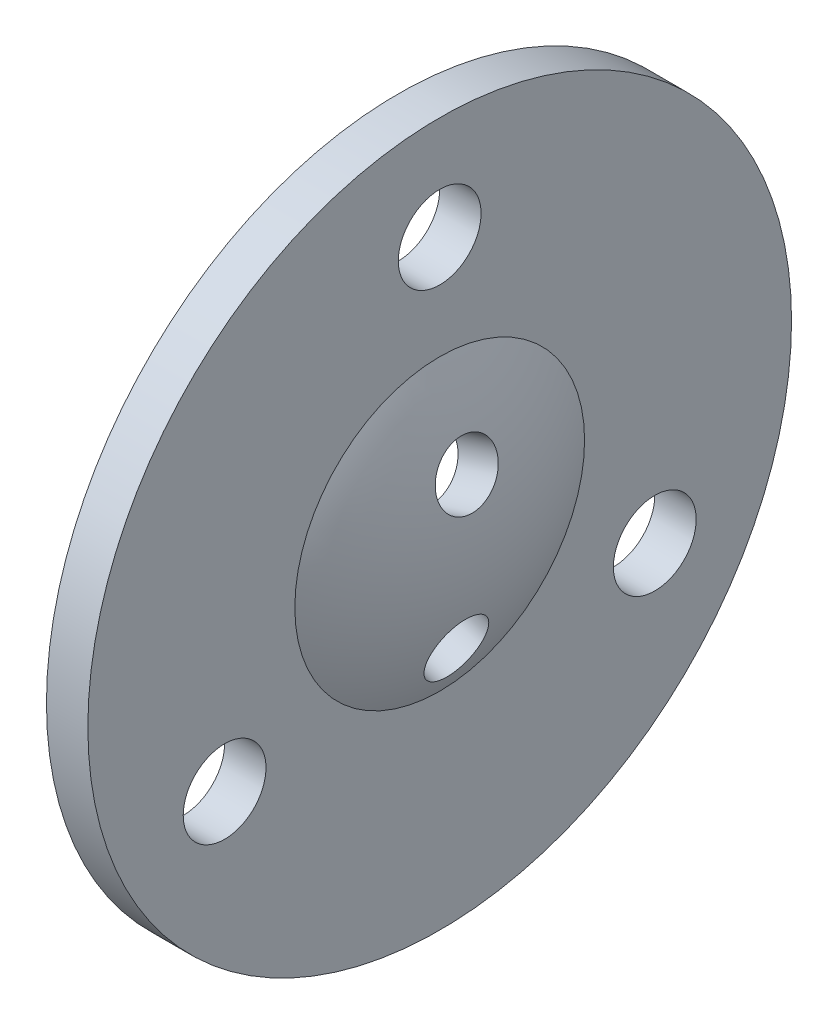
SolidWorks part; units mm, degrees
material "铝棒 LY12"
ref_plane "前视基准面" through (0, 0, 0) normal (0, 0, 1) x (1, 0, 0)
ref_plane "上视基准面" through (0, 0, 0) normal (0, 1, 0) x (1, 0, 0)
ref_plane "右视基准面" through (0, 0, 0) normal (1, 0, 0) x (0, 0, -1)
sketch "草图1" plane through (0, 0, 0) normal (0, 0, 1) x (1, 0, 0)
  line L0 (14.3875, 7) -> (14.3875, 17)
  line L1 (14.3875, 17) -> (12.3875, 17)
  line L2 (12.3875, 17) -> (12.3875, 6.523)
  line L3 (0, 0) -> (19.0099, 0) construction
  line L4 (14, 0) -> (16, 0)
  arc A0 (14, 0) -> (12.3875, 6.523) centre (0, 0) ccw
  arc A1 (16, 0) -> (14.3875, 7) centre (0, 0) ccw
  circle A2 centre (0, 0) radius 16 construction
  circle A3 centre (0, 0) radius 14 construction
  dimension "D2" = 28
  dimension "D3" = 2
  dimension "D4" = 17
  dimension "D5" = 14
  dimension "D1" = 2
revolve "旋转1" add sketch "草图1" angle 360 about L3
sketch "草图2" plane through (12.3875, 0, 0) normal (-1, 0, 0) x (0, 0, 1)
  line L0 (0, 0) -> (0, 12)
  circle A0 centre (0, 0) radius 12 construction
  circle A1 centre (0, 12) radius 2
  circle A2 centre (10.3923, -6) radius 2
  circle A3 centre (-10.3923, -6) radius 2
  dimension "D1" = 24
  dimension "D2" = 4
  dimension "D3" = 3
extrude "切除-拉伸1" cut sketch "草图2" against normal blind 10 contours A3 | A1 | A2
sketch "草图7" plane through (0, 0, 0) normal (0, 0, 1) x (1, 0, 0)
  line L0 (7.0543, 0) -> (18.2599, 3.5331)
  line L1 (7.0543, 0) -> (21.271, -4.4825)
  line L2 (7.0543, 0) -> (15.1673, 0)
  point P2 (0, 0)
  dimension "D1" = 17.5
  dimension "D2" = 17.5
ref_plane "基准面3" through (18.2599, 3.5331, 0) normal (0.9537, 0.3007, 0) x (0, 0, -1)
sketch "草图8" plane through (18.2599, 3.5331, 0) normal (0.9537, 0.3007, 0) x (0, 0, -1)
  line L0 (0, 0) -> (0, -2.4396) construction
  line L1 (0, 0) -> (0, -8.5501) construction
  circle A0 centre (0, 0) radius 1.5
  dimension "D1" = 3
extrude "切除-拉伸4" cut sketch "草图8" against normal blind 10
ref_plane "基准面5" through (21.271, -4.4825, 0) normal (0.9537, -0.3007, 0) x (0, 0, -1)
sketch "草图9" plane through (21.271, -4.4825, 0) normal (0.9537, -0.3007, 0) x (0, 0, -1)
  circle A0 centre (0, -2.1213) radius 1.5
  dimension "D1" = 3
extrude "切除-拉伸5" cut sketch "草图9" against normal blind 10
